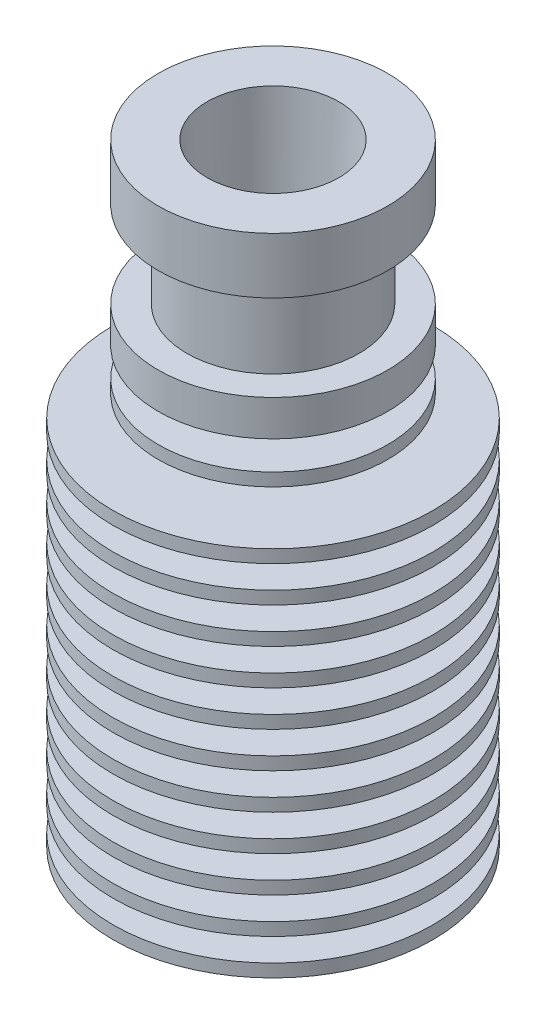
SolidWorks part; units mm, degrees
ref_plane "前视" through (0, 0, 0) normal (0, 0, 1) x (1, 0, 0)
ref_plane "上视" through (0, 0, 0) normal (0, 1, 0) x (1, 0, 0)
ref_plane "右视" through (0, 0, 0) normal (1, 0, 0) x (0, 0, -1)
sketch "草图1" plane through (0, 0, 0) normal (0, 0, 1) x (1, 0, 0)
  line L0 (0, 0) -> (11.15, 0)
  line L1 (11.15, 0) -> (11.15, 0.9)
  line L2 (11.15, 0.9) -> (7, 0.9)
  line L3 (7, 0.9) -> (7, 2.5)
  line L4 (7, 2.5) -> (11.15, 2.5)
  line L5 (11.15, 2.5) -> (11.15, 3.4)
  line L6 (11.15, 3.4) -> (6.5, 3.4)
  line L7 (6.5, 3.4) -> (6.5, 5)
  line L8 (6.5, 5) -> (11.15, 5)
  line L9 (11.15, 5) -> (11.15, 5.9)
  line L10 (11.15, 5.9) -> (6.3, 5.9)
  line L11 (6.3, 5.9) -> (6.3, 7.5)
  line L12 (6.3, 7.5) -> (11.15, 7.5)
  line L13 (11.15, 7.5) -> (11.15, 8.4)
  line L14 (11.15, 8.4) -> (6.1, 8.4)
  line L15 (6.1, 8.4) -> (6.1, 10)
  line L16 (6.1, 10) -> (11.15, 10)
  line L17 (11.15, 10) -> (11.15, 10.9)
  line L18 (11.15, 10.9) -> (5.9, 10.9)
  line L19 (5.9, 10.9) -> (5.9, 12.5)
  line L20 (4.7, 27.4) -> (8, 27.4)
  line L21 (8, 27.4) -> (8, 28.3)
  line L22 (8, 28.3) -> (4.5, 28.3)
  line L23 (4.5, 28.3) -> (4.5, 30.3)
  line L24 (4.5, 30.3) -> (8, 30.3)
  line L25 (8, 30.3) -> (8, 32.8)
  line L26 (8, 32.8) -> (6, 32.8)
  line L27 (6, 32.8) -> (6, 38.8)
  line L28 (6, 38.8) -> (8, 38.8)
  line L29 (8, 38.8) -> (8, 42.7)
  line L30 (8, 42.7) -> (0, 42.7)
  line L31 (0, 42.7) -> (0, 0)
  line L32 (5.9, 12.5) -> (11.15, 12.5)
  line L33 (11.15, 12.5) -> (11.15, 13.4)
  line L34 (11.15, 13.4) -> (5.7, 13.4)
  line L35 (5.7, 13.4) -> (5.7, 15)
  line L36 (5.7, 15) -> (11.15, 15)
  line L37 (11.15, 15) -> (11.15, 15.9)
  line L38 (11.15, 15.9) -> (5.5, 15.9)
  line L39 (5.5, 17.5) -> (5.5, 15.9)
  line L40 (5.5, 17.5) -> (11.15, 17.5)
  line L41 (11.15, 17.5) -> (11.15, 18.4)
  line L42 (11.15, 18.4) -> (5.3, 18.4)
  line L43 (5.3, 18.4) -> (5.3, 20)
  line L44 (5.3, 20) -> (11.15, 20)
  line L45 (11.15, 20) -> (11.15, 20.9)
  line L46 (11.15, 20.9) -> (5.1, 20.9)
  line L47 (5.1, 22.5) -> (5.1, 20.9)
  line L48 (11.15, 0) -> (11.15, 33) construction
  line L49 (11.15, 33) -> (11.15, 0) construction
  line L50 (5.1, 22.5) -> (11.15, 22.5)
  line L51 (11.15, 22.5) -> (11.15, 23.4)
  line L52 (11.15, 23.4) -> (4.9, 23.4)
  line L53 (4.9, 23.4) -> (4.9, 25)
  line L54 (4.9, 25) -> (11.15, 25)
  line L55 (11.15, 25) -> (11.15, 25.9)
  line L56 (11.15, 25.9) -> (4.7, 25.9)
  line L57 (4.7, 25.9) -> (4.7, 27.4)
  line L58 (11.15, 0) -> (11.15, 25.9) construction
  line L59 (11.15, 0) -> (11.15, 26) construction
  point P61 (0, 0)
  dimension "D2" = 3.9
  dimension "D3" = 6
  dimension "D4" = 2.5
  dimension "D5" = 0.9
  dimension "D6" = 1.6
  dimension "D7" = 42.7
  dimension "D8" = 0.9
  dimension "D9" = 4.5
  dimension "D10" = 8
  dimension "D11" = 2
  dimension "D12" = 0.9
  dimension "D13" = 11.15
  dimension "D14" = 11.15
  dimension "D15" = 4.15
  dimension "D16" = 4.15
  dimension "D17" = 0.9
  dimension "D18" = 0.9
  dimension "D19" = 6.3
  dimension "D20" = 0
  dimension "D21" = 0
  dimension "D22" = 0
  dimension "D23" = 0
  dimension "D24" = 1.6
  dimension "D25" = 0
  dimension "D26" = 0
  dimension "D27" = 1.6
  dimension "D28" = 1.6
  dimension "D29" = 5.7
  dimension "D30" = 4.7
  dimension "D31" = 4.9
  dimension "D32" = 5.1
  dimension "D33" = 5.3
  dimension "D34" = 5.5
  dimension "D35" = 5.9
  dimension "D36" = 6.1
  dimension "D37" = 6.5
  dimension "D38" = 11.15
  dimension "D39" = 11.15
  dimension "D40" = 11.15
revolve "旋转1" add sketch "草图1" angle 360 about L31
hole_wizard "1/8 Rc 螺纹孔1" positions "草图3" profile "草图2" size "1/8" standard "Gb"
sketch "草图3" plane through (0, 42.7, 0) normal (0, 1, 0) x (1, 0, 0)
  point P0 (0, 0)
sketch "草图2" plane through (0, 42.7, 0) normal (1, 0, 0) x (0, 0, 1)
  line L0 (0, 0) -> (0, 11.3734)
  line L1 (3.95, 9) -> (0, 11.3734)
  line L2 (-3.95, 9) -> (0, 11.3734) construction
  line L3 (3.95, 9) -> (3.95, 8)
  line L4 (3.95, 8) -> (4.3425, 8)
  line L5 (4.3425, 8) -> (4.5922, 0)
  line L6 (-4.3425, 8) -> (-4.5922, 0) construction
  line L7 (4.5922, 0) -> (0, 0)
  line L8 (0, -6.35) -> (0, 107.95) construction
  line L11 (-3.95, 8) -> (-4.3425, 8) construction
  dimension "螺纹孔钻头直径" = 7.9
  dimension "螺纹孔钻头深度" = 9
  dimension "螺纹直径" = 9.1845
  dimension "螺纹角度" = 3.576
  dimension "螺纹深度" = 8
  dimension "导头角度" = 118
cosmetic thread "孔螺蚊线1" parameters "D1"=8, "D2"=11.7655
hole_wizard "M7x1.0 螺纹孔1" positions "草图5" profile "草图4" tap size "M7x1.0" standard "JIS"
sketch "草图5" plane through (0, 0, 0) normal (0, -1, 0) x (-1, 0, 0)
  point P0 (0, 0)
sketch "草图4" plane through (0, 0, 0) normal (1, 0, 0) x (0, 0, -1)
  line L0 (0, 0) -> (0, 15)
  line L1 (0, 15) -> (3, 15)
  line L2 (3, 15) -> (3, 0)
  line L5 (3, 0) -> (0, 0)
  line L10 (0, 15) -> (-3, 15) construction
  line L11 (0, -6.35) -> (0, 107.95) construction
  dimension "螺纹孔钻头直径" = 6
  dimension "螺纹孔钻头深度" = 15
  dimension "导头角度" = 180
cosmetic thread "孔螺蚊线2" parameters "D1"=15, "D2"=7
sketch "草图6" plane through (0, 15, 0) normal (0, -1, 0) x (1, 0, 0)
  circle A0 centre (0, 0) radius 1
  dimension "D1" = 2
extrude "切除-拉伸1" cut sketch "草图6" against normal blind 15
sketch "草图7" plane through (0, 0, 0) normal (0, 0, 1) x (1, 0, 0)
  line L0 (0, 32.8) -> (0, 30.3) construction
  line L1 (8, 32.8) -> (-8, 32.8) construction
  line L2 (-4.5, 30.3) -> (4.5, 30.3) construction
  line L3 (-7, 29.55) -> (-9, 29.55)
  line L4 (7, 29.55) -> (-7, 29.55) construction
  line L5 (7, 29.55) -> (7, 33.55)
  line L6 (7, 33.55) -> (-7, 33.55) construction
  line L7 (-7, 29.55) -> (-7, 33.55)
  line L8 (7, 29.55) -> (-7, 33.55) construction
  line L9 (7, 33.55) -> (-7, 29.55) construction
  line L10 (-9, 29.55) -> (-9, 33.55)
  line L11 (-9, 33.55) -> (-7, 33.55)
  line L12 (7, 33.55) -> (9, 33.55)
  line L13 (9, 33.55) -> (9, 29.55)
  line L14 (9, 29.55) -> (7, 29.55)
  point P6 (0, 31.55)
  dimension "D1" = 14
  dimension "D2" = 4
  dimension "D3" = 2
  dimension "D4" = 2
sketch "草图8" plane through (0, 42.7, 0) normal (0, 1, 0) x (1, 0, 0)
  circle A0 centre (0, 0) radius 4
extrude "切除-拉伸2" cut sketch "草图8" against normal through all and the other way through all
